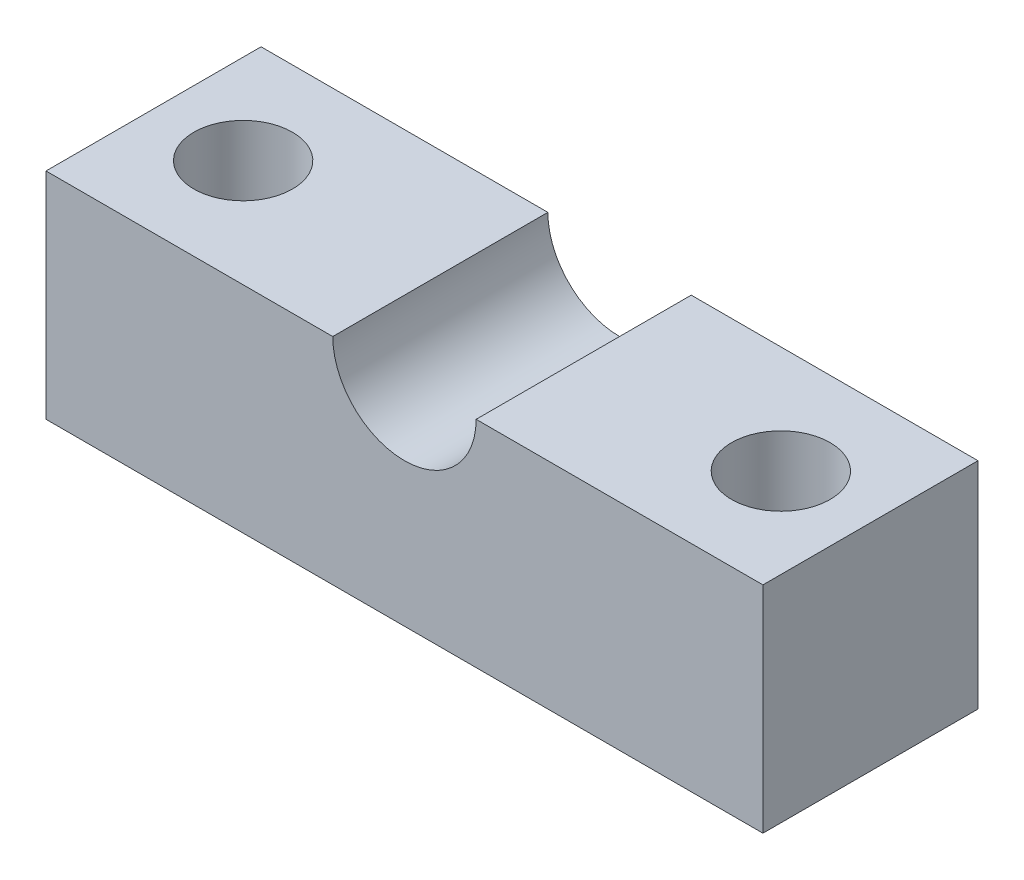
SolidWorks part; units mm, degrees
ref_plane "Ebene vorne" through (0, 0, 0) normal (0, 0, 1) x (1, 0, 0)
ref_plane "Ebene oben" through (0, 0, 0) normal (0, 1, 0) x (1, 0, 0)
ref_plane "Ebene rechts" through (0, 0, 0) normal (1, 0, 0) x (0, 0, -1)
sketch "Skizze1" plane through (0, 0, 0) normal (0, 0, 1) x (1, 0, 0)
  line L0 (24, 12) -> (40, 12)
  line L1 (0, 0) -> (40, 0)
  line L2 (0, 0) -> (0, 12)
  line L3 (0, 12) -> (16, 12)
  line L4 (40, 0) -> (40, 12)
  arc A0 (16, 12) -> (24, 12) centre (20, 12) ccw
  dimension "D3" = 8
  dimension "D1" = 40
  dimension "D2" = 12
extrude "Aufsatz-Linear austragen1" add sketch "Skizze1" along normal blind 12
hole_wizard "Ø5.5 (5.5) Durchmesser Bohrung1" positions "Skizze2" profile "Skizze3" hole size "Ø5.5" standard "ISO" end condition through all
sketch "Skizze2" plane through (0, 0, 0) normal (0, -1, 0) x (-1, 0, 0)
  line L0 (0, -12) -> (-40, -12) construction
  line L1 (0, -12) -> (0, 0) construction
  point P0 (-5, -6)
  point P2 (-35, -6)
  dimension "D1" = 6
  dimension "D2" = 6
  dimension "D3" = 5
  dimension "D4" = 5
sketch "Skizze3" plane through (5, 0, 6) normal (1, 0, 0) x (0, 0, -1)
  line L0 (0, 0) -> (0, 12)
  line L1 (0, 12) -> (2.75, 12)
  line L2 (2.75, 12) -> (2.75, 0)
  line L5 (2.75, 0) -> (0, 0)
  line L11 (0, -6.35) -> (0, 107.95) construction
  dimension "Bohrerdurchmesser" = 5.5
  dimension "Bohrungstiefe" = 12
